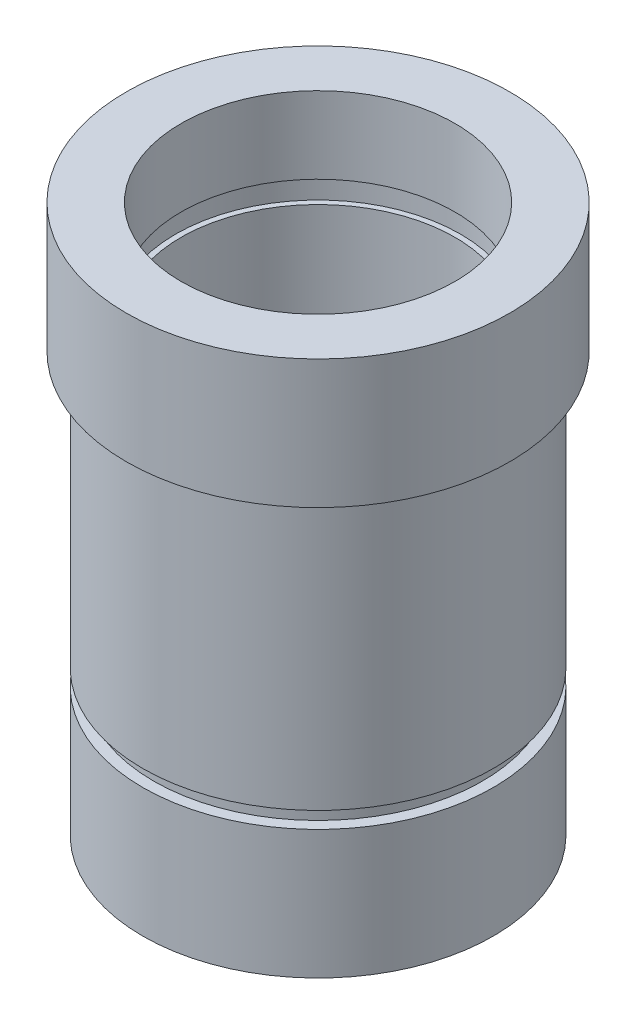
SolidWorks part; units mm, degrees
material "Beryllium S-200F, Vacuum Hot Pressed"
ref_plane "Front Plane" through (0, 0, 0) normal (0, 0, 1) x (1, 0, 0)
ref_plane "Top Plane" through (0, 0, 0) normal (0, 1, 0) x (1, 0, 0)
ref_plane "Right Plane" through (0, 0, 0) normal (1, 0, 0) x (0, 0, -1)
sketch "Sketch1" plane through (0, 0, 0) normal (0, 0, 1) x (1, 0, 0)
  line L0 (0, 23.3627) -> (0, -31.0453) construction
  line L1 (0, 23.1321) -> (17.5, 23.1321)
  line L2 (17.5, 23.1321) -> (17.5, 11.3821)
  line L3 (17.5, 11.3821) -> (16, 11.3821)
  line L4 (16, 11.3821) -> (16, -13.6179)
  line L5 (16, -13.6179) -> (15, -13.6179)
  line L6 (15, -13.6179) -> (15, -15.1179)
  line L7 (15, -15.1179) -> (16, -15.1179)
  line L8 (16, -15.1179) -> (16, -26.8679)
  line L9 (16, -26.8679) -> (0, -26.8679)
  line L10 (0, -26.8679) -> (0, 23.1321)
  point P12 (0.7282, -13.6895)
  point P14 (0, 0)
  point P15 (13.4894, -13.6179)
  dimension "D1" = 50
  dimension "D2" = 11.75
  dimension "D3" = 11.75
  dimension "D4" = 25
  dimension "D5" = 1.5
  dimension "D6" = 17.5
  dimension "D7" = 16
  dimension "D8" = 1.5
  dimension "D9" = 1
revolve "Revolve1" add sketch "Sketch1" angle 360 about L0
sketch "Sketch2" plane through (0, 23.1321, 0) normal (0, 1, 0) x (1, 0, 0)
  circle A0 centre (0, 0) radius 12.5
  dimension "D1" = 25
extrude "Cut-Extrude1" cut sketch "Sketch2" against normal through all
ref_plane "Plane1" through (0, 16.1321, 0) normal (0, 1, 0) x (1, 0, 0)
sketch "Sketch3" plane through (0, 16.1321, 0) normal (0, 1, 0) x (1, 0, 0)
  circle A0 centre (0, 0) radius 13
  dimension "D1" = 26
extrude "Cut-Extrude2" cut sketch "Sketch3" against normal blind 2
ref_plane "Plane2" through (0, -19.8679, 0) normal (0, -1, 0) x (-1, 0, 0)
sketch "Sketch4" plane through (0, -19.8679, 0) normal (0, -1, 0) x (-1, 0, 0)
  circle A0 centre (0, 0) radius 13
  dimension "D1" = 26
extrude "Cut-Extrude3" cut sketch "Sketch4" against normal blind 2
